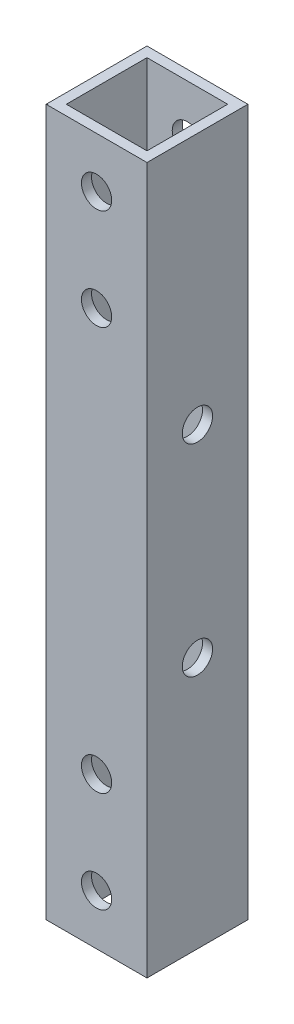
SolidWorks part; units mm, degrees
material "氧化铝"
ref_plane "前视基准面" through (0, 0, 0) normal (0, 0, 1) x (1, 0, 0)
ref_plane "上视基准面" through (0, 0, 0) normal (0, 1, 0) x (1, 0, 0)
ref_plane "右视基准面" through (0, 0, 0) normal (1, 0, 0) x (0, 0, -1)
other "Configuration Table"
sketch "草图1" plane through (0, 0, 0) normal (0, 1, 0) x (1, 0, 0)
  line L1 (-4, 4) -> (4, 4)
  line L2 (-4, 4) -> (-4, -4)
  line L3 (-4, -4) -> (4, -4)
  line L4 (4, 4) -> (4, -4)
  line L5 (-4, 4) -> (4, -4) construction
  line L6 (-4, -4) -> (4, 4) construction
  line L7 (-5, 5) -> (5, 5)
  line L8 (-5, 5) -> (-5, -5)
  line L9 (-5, -5) -> (5, -5)
  line L10 (5, 5) -> (5, -5)
  line L11 (-5, 5) -> (5, -5) construction
  line L12 (-5, -5) -> (5, 5) construction
  point P0 (0, 0)
  point P6 (0, 0)
  dimension "D1" = 1
  dimension "D2" = 1
  dimension "D3" = 10
  dimension "D4" = 10
extrude "凸台-拉伸1" add sketch "草图1" along normal blind 70
sketch "草图2" plane through (-5, 0, 0) normal (-1, 0, 0) x (0, 0, 1)
  line L0 (0, 0) -> (0, 70) construction
  line L1 (-5, 70) -> (5, 70) construction
  line L2 (5, 35) -> (-5, 35) construction
  line L3 (-5, 70) -> (-5, 0) construction
  line L4 (5, 70) -> (5, 0) construction
  circle A0 centre (0, 25) radius 1.5
  circle A1 centre (0, 45) radius 1.5
  point P9 (5, 35)
  dimension "D2" = 3
  dimension "D1" = 20
extrude "切除-拉伸1" cut sketch "草图2" against normal blind 30
sketch "草图3" plane through (0, 0, -5) normal (0, 0, -1) x (-1, 0, 0)
  line L0 (0, 0) -> (0, 70) construction
  line L1 (-5, 70) -> (5, 70) construction
  line L2 (-5, 35) -> (5, 35) construction
  line L3 (-5, 70) -> (-5, 0) construction
  line L4 (5, 70) -> (5, 0) construction
  circle A0 centre (0, 65) radius 1.5
  circle A1 centre (0, 55) radius 1.5
  circle A2 centre (0, 15) radius 1.5
  circle A3 centre (0, 5) radius 1.5
  dimension "D2" = 3
  dimension "D1" = 10
  dimension "D3" = 5
extrude "切除-拉伸2" cut sketch "草图3" against normal blind 30
